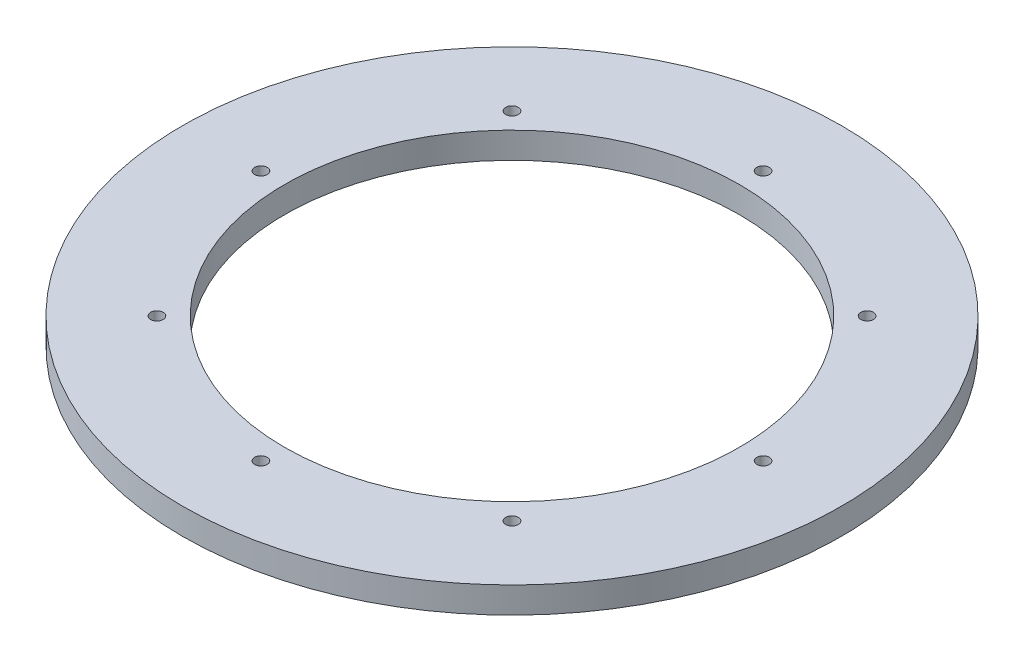
SolidWorks part; units mm, degrees
material "Custom Plastic"
ref_plane "Front Plane" through (0, 0, 0) normal (0, 0, 1) x (1, 0, 0)
ref_plane "Top Plane" through (0, 0, 0) normal (0, 1, 0) x (1, 0, 0)
ref_plane "Right Plane" through (0, 0, 0) normal (1, 0, 0) x (0, 0, -1)
sketch "Sketch1" plane through (0, 0, 0) normal (0, 1, 0) x (1, 0, 0)
  line L0 (0, -7310.1215) -> (0, 358195.9516) construction
  line L1 (-7310.1215, 0) -> (358195.9516, 0) construction
  circle A0 centre (0, 0) radius 315
  circle A1 centre (0, 0) radius 217.5
  circle A2 centre (0, 240) radius 6
  circle A3 centre (169.7056, 169.7056) radius 6
  circle A4 centre (240, 0) radius 6
  circle A5 centre (169.7056, -169.7056) radius 6
  circle A6 centre (0, -240) radius 6
  circle A7 centre (-169.7056, -169.7056) radius 6
  circle A8 centre (-240, 0) radius 6
  circle A9 centre (-169.7056, 169.7056) radius 6
  point P27 (0, 0)
  dimension "D1" = 630
  dimension "D2" = 435
  dimension "D4" = 12
  dimension "D6" = 240
  dimension "D3" = 240
  dimension "D5" = 8
extrude "Boss-Extrude1" add sketch "Sketch1" along normal mid plane 25
